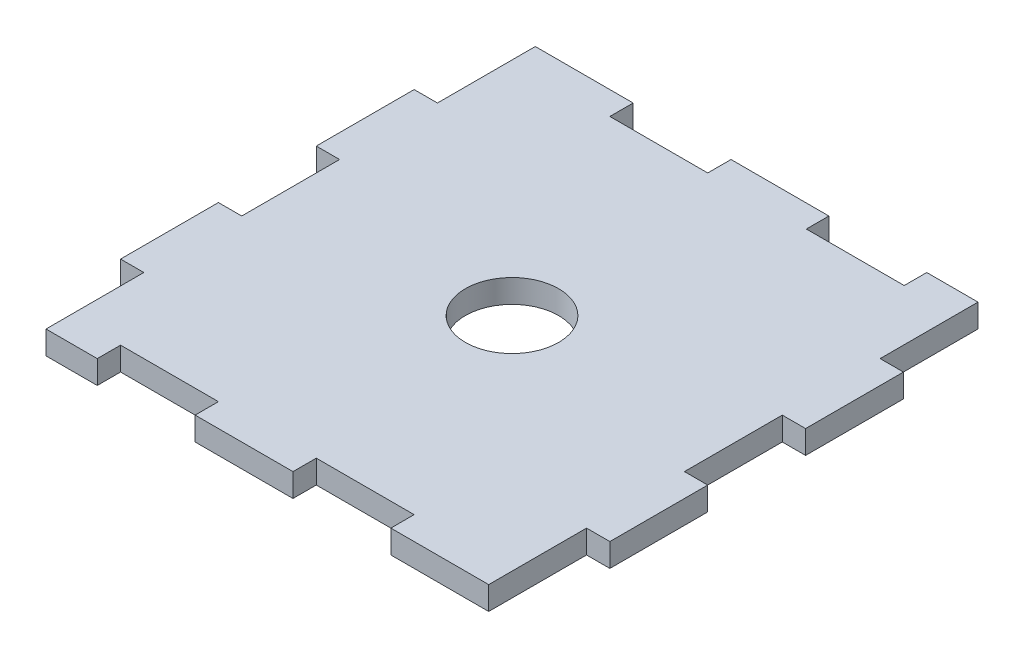
SolidWorks part; units mm, degrees
ref_plane "Front Plane" through (0, 0, 0) normal (0, 0, 1) x (1, 0, 0)
ref_plane "Top Plane" through (0, 0, 0) normal (0, 1, 0) x (1, 0, 0)
ref_plane "Right Plane" through (0, 0, 0) normal (1, 0, 0) x (0, 0, -1)
sketch "Sketch2" plane through (0, 100, 0) normal (0, 1, 0) x (1, 0, 0)
  line L0 (60, 95.3929) -> (80, 95.3929)
  line L36 (40, 100) -> (40, 95.2375)
  line L37 (40, 95.2375) -> (20, 95.2375)
  line L38 (20, 95.2375) -> (20, 100)
  line L39 (20, 100) -> (0, 100)
  line L40 (0, 100) -> (0, 80)
  line L41 (0, 80) -> (-4.7625, 80)
  line L42 (-4.7625, 80) -> (-4.7625, 60)
  line L43 (-4.7625, 60) -> (0, 60)
  line L44 (0, 60) -> (0, 40)
  line L45 (0, 40) -> (-4.7625, 40)
  line L46 (-4.7625, 40) -> (-4.7625, 20)
  line L47 (-4.7625, 20) -> (0, 20)
  line L48 (0, 20) -> (0, 0)
  line L49 (0, 0) -> (10.475, 0)
  line L50 (10.475, 0) -> (10.475, 4.7625)
  line L51 (10.475, 4.7625) -> (30.475, 4.7625)
  line L52 (30.475, 4.7625) -> (30.475, 0)
  line L53 (30.475, 0) -> (50.475, 0)
  line L54 (50.475, 0) -> (50.475, 4.7625)
  line L55 (50.475, 4.7625) -> (70.475, 4.7625)
  line L56 (70.475, 4.7625) -> (70.475, 0)
  line L57 (70.475, 0) -> (90.475, 0)
  line L58 (90.475, 0) -> (90.475, 20)
  line L59 (90.475, 20) -> (95.2375, 20)
  line L60 (95.2375, 20) -> (95.2375, 40)
  line L61 (95.2375, 40) -> (90.475, 40)
  line L62 (90.475, 40) -> (90.475, 60)
  line L63 (90.475, 60) -> (95.2375, 60)
  line L64 (95.2375, 60) -> (95.2375, 80)
  line L65 (95.2375, 80) -> (90.475, 80)
  line L66 (90.475, 80) -> (90.475, 100)
  line L67 (90.475, 100) -> (80, 100)
  line L68 (80, 100) -> (80, 95.2375)
  line L69 (80, 95.2375) -> (76.9625, 95.2375)
  line L70 (60, 95.3929) -> (60, 100)
  line L71 (60, 100) -> (40, 100)
  line L72 (40, 100) -> (40, 95.2375)
  line L73 (40, 95.2375) -> (20, 95.2375)
  line L74 (20, 95.2375) -> (20, 100)
  line L75 (20, 100) -> (0, 100)
  line L76 (0, 100) -> (0, 80)
  line L77 (0, 80) -> (-4.7625, 80)
  line L78 (-4.7625, 80) -> (-4.7625, 60)
  line L79 (-4.7625, 60) -> (0, 60)
  line L80 (0, 60) -> (0, 40)
  line L81 (0, 40) -> (-4.7625, 40)
  line L82 (-4.7625, 40) -> (-4.7625, 20)
  line L83 (-4.7625, 20) -> (0, 20)
  line L84 (0, 20) -> (0, 0)
  line L85 (0, 0) -> (10.475, 0)
  line L86 (10.475, 0) -> (10.475, 4.7625)
  line L87 (10.475, 4.7625) -> (30.475, 4.7625)
  line L88 (30.475, 4.7625) -> (30.475, 0)
  line L89 (30.475, 0) -> (50.475, 0)
  line L90 (50.475, 0) -> (50.475, 4.7625)
  line L91 (50.475, 4.7625) -> (70.475, 4.7625)
  line L92 (70.475, 4.7625) -> (70.475, 0)
  line L93 (70.475, 0) -> (90.475, 0)
  line L94 (90.475, 0) -> (90.475, 20)
  line L95 (90.475, 20) -> (95.2375, 20)
  line L96 (95.2375, 20) -> (95.2375, 40)
  line L97 (95.2375, 40) -> (90.475, 40)
  line L98 (90.475, 40) -> (90.475, 60)
  line L99 (90.475, 60) -> (95.2375, 60)
  line L100 (95.2375, 60) -> (95.2375, 80)
  line L101 (95.2375, 80) -> (90.475, 80)
  line L102 (90.475, 80) -> (90.475, 100)
  line L103 (90.475, 100) -> (80, 100)
  line L104 (80, 100) -> (80, 95.2375)
  line L107 (60, 100) -> (40, 100)
  line L185 (55.1899, 54.3869) -> (55.1899, 95.3929)
  line L187 (76.9625, 95.2375) -> (76.9625, 54.3869)
  line L269 (60, 95.3929) -> (60, 100)
  line L270 (55.1899, 95.3929) -> (60, 95.3929)
  line L271 (55.1899, 95.3929) -> (60, 95.3929)
  line L272 (60, 54.3869) -> (55.1899, 54.3869)
  line L635 (76.9625, 54.3869) -> (72.1524, 54.3869)
  line L637 (72.1524, 54.3869) -> (72.1524, 54.5899)
  line L639 (72.1524, 54.5899) -> (60, 54.5899)
  line L641 (60, 54.5899) -> (60, 54.3869)
  dimension "D1" = 0
extrude "Boss-Extrude1" add sketch "Sketch2" against normal blind 4.7625
sketch "Sketch3" plane through (0, 100, 0) normal (0, 1, 0) x (1, 0, 0)
  circle A0 centre (45.2375, 50) radius 9.525 construction
  circle A1 centre (45.2375, 50) radius 9.525
extrude "Cut-Extrude1" cut sketch "Sketch3" against normal blind 4.7625
